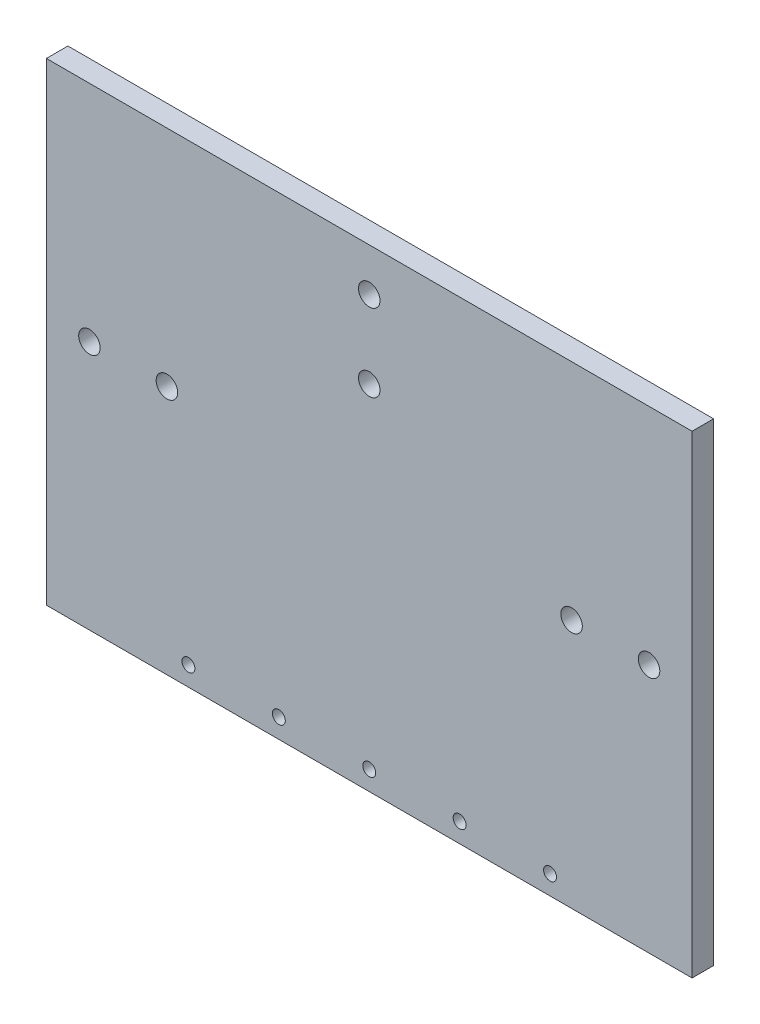
SolidWorks part; units mm, degrees
ref_plane "前基準面" through (0, 0, 0) normal (0, 0, 1) x (1, 0, 0)
ref_plane "上基準面" through (0, 0, 0) normal (0, 1, 0) x (1, 0, 0)
ref_plane "右基準面" through (0, 0, 0) normal (1, 0, 0) x (0, 0, -1)
sketch "草圖1" plane through (0, 0, 0) normal (0, 0, 1) x (1, 0, 0)
  line L1 (-75, 55) -> (75, 55)
  line L2 (-75, 55) -> (-75, -55)
  line L3 (-75, -55) -> (75, -55)
  line L4 (75, 55) -> (75, -55)
  line L5 (-75, 55) -> (75, -55) construction
  line L6 (-75, -55) -> (75, 55) construction
  point P0 (0, 0)
  dimension "D1" = 110
  dimension "D2" = 150
extrude "填料-伸長1" add sketch "草圖1" along normal blind 5
sketch "草圖2" plane through (0, 0, 5) normal (0, 0, 1) x (1, 0, 0)
  line L0 (-75, -55) -> (75, -55) construction
  line L1 (75, -55) -> (75, 55) construction
  circle A0 centre (42, -50.5) radius 1.5
  dimension "D1" = 3
  dimension "D2" = 4.5
  dimension "D3" = 33
extrude "除料-伸長1" cut sketch "草圖2" against normal up to next
pattern_linear "直線複製排列1" count 5 spacing 21 along (-1, 0, 0) of "除料-伸長1"
sketch "草圖3" plane through (0, 0, 5) normal (0, 0, 1) x (1, 0, 0)
  line L0 (-75, 55) -> (-75, -55) construction
  line L1 (75, -55) -> (75, 55) construction
  line L2 (-75, 52) -> (75, 52) construction
  line L3 (-75, 52) -> (-75, -46) construction
  line L4 (-75, -46) -> (75, -46) construction
  line L5 (75, 52) -> (75, -46) construction
  line L6 (-75, -55) -> (75, -55) construction
  line L7 (75, 55) -> (-75, 55) construction
  circle A0 centre (-65, 3) radius 2.5
  circle A1 centre (-47, 3) radius 2.5
  point P17 (-75, 3)
  dimension "D1" = 5
  dimension "D3" = 18
  dimension "D2" = 10
  dimension "D4" = 9
  dimension "D5" = 3
extrude "除料-伸長2" cut sketch "草圖3" against normal up to next
mirror "鏡射1" about plane through (0, 0, 0) normal (1, 0, 0) of "除料-伸長2"
sketch "草圖4" plane through (0, 0, 5) normal (0, 0, 1) x (1, 0, 0)
  line L0 (75, 55) -> (-75, 55) construction
  circle A0 centre (0, 45) radius 2.5
  circle A1 centre (0, 27) radius 2.5
  dimension "D1" = 5
  dimension "D2" = 10
  dimension "D3" = 18
extrude "除料-伸長3" cut sketch "草圖4" against normal up to next
